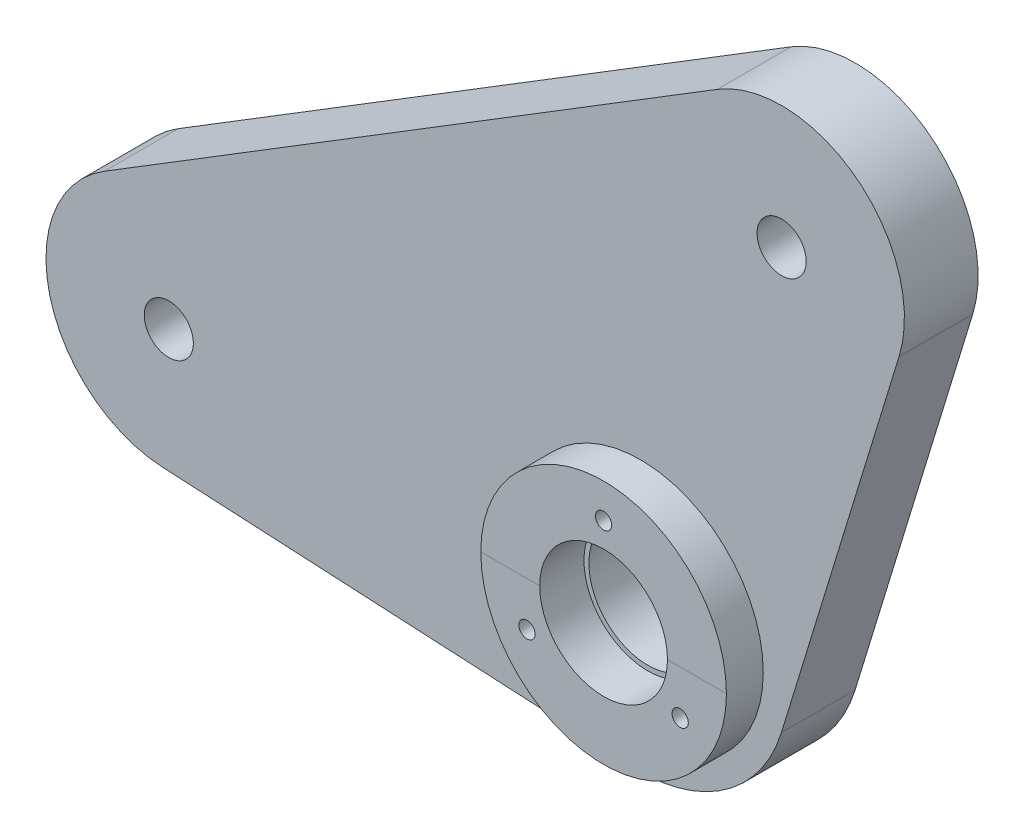
SolidWorks part; units mm, degrees
material "6061-T6 (SS)"
ref_plane "Front Plane" through (0, 0, 0) normal (0, 0, 1) x (1, 0, 0)
ref_plane "Top Plane" through (0, 0, 0) normal (0, 1, 0) x (1, 0, 0)
ref_plane "Right Plane" through (0, 0, 0) normal (1, 0, 0) x (0, 0, -1)
sketch "Layout_Reference" plane through (0, 0, 0) normal (0, 0, 1) x (1, 0, 0)
  line L0 (0, 0) -> (-96, 0) construction
  line L1 (0, 0) -> (28.736, 76.8) construction
  line L2 (-96, 0) -> (-232.8081, -375.877) construction
  line L3 (28.736, 76.8) -> (328.736, 76.8) construction
  dimension "D1" = 96
  dimension "D2" = 82
  dimension "D3" = 76.8
  dimension "D4" = 400
  dimension "D5" = 70
  dimension "D6" = 300
sketch "Rocker_Profile" plane through (0, 0, 0) normal (0, 0, 1) x (1, 0, 0)
  line L0 (-97.3021, -24.9661) -> (-1.5625, -29.9593)
  line L1 (28.6863, -8.7804) -> (52.6413, 69.483)
  line L2 (-109.1073, 21.2885) -> (15.6287, 98.0885)
  arc A0 (-1.5625, -29.9593) -> (28.6863, -8.7804) centre (0, 0) ccw
  arc A1 (52.6413, 69.483) -> (15.6287, 98.0885) centre (28.736, 76.8) ccw
  arc A2 (-109.1073, 21.2885) -> (-97.3021, -24.9661) centre (-96, 0) ccw
  dimension "D1" = 60
  dimension "D2" = 50
  dimension "D3" = 50
extrude "Baseline_Body" add sketch "Rocker_Profile" along normal mid plane 15
sketch "Sketch3" plane through (0, 0, 7.5) normal (0, 0, 1) x (1, 0, 0)
  circle A0 centre (-96, 0) radius 5
  circle A1 centre (28.736, 76.8) radius 5
  dimension "D1" = 10
  dimension "D2" = 10
extrude "Cut-Extrude1" cut sketch "Sketch3" against normal through all
sketch "Sketch4" plane through (0, 0, 0) normal (0, 0, 1) x (1, 0, 0)
  circle A0 centre (0, 0) radius 25
  dimension "D1" = 50
extrude "Boss-Extrude2" add sketch "Sketch4" along normal mid plane 30
sketch "Sketch5" plane through (0, 0, 15) normal (0, 0, 1) x (1, 0, 0)
  circle A0 centre (0, 0) radius 12
  dimension "D1" = 24
extrude "Cut-Extrude2" cut sketch "Sketch5" against normal through all
sketch "Sketch6" plane through (0, 0, 15) normal (0, 0, 1) x (1, 0, 0)
  circle A0 centre (0, 0) radius 13
  dimension "D1" = 26
extrude "Cut-Extrude3" cut sketch "Sketch6" against normal blind 9
sketch "Sketch7" plane through (0, 0, -15) normal (0, 0, -1) x (-1, 0, 0)
  circle A0 centre (0, 0) radius 13
  dimension "D1" = 26
extrude "Cut-Extrude4" cut sketch "Sketch7" against normal blind 9
hole_wizard "M4 Tapped Hole6" positions "Sketch13" profile "Sketch14" tap size "M4" standard "ISO"
sketch "Sketch13" plane through (0, 0, 15) normal (0, 0, 1) x (1, 0, 0)
  line L0 (0, 0) -> (0, 35.402) construction
  line L2 (0, 0) -> (31.5691, -18.2264) construction
  line L4 (0, 0) -> (-31.7239, -18.3158) construction
  circle A0 centre (0, 0) radius 18
  point P20 (0, 18)
  point P22 (15.5885, -9)
  point P24 (-15.5885, -9)
  dimension "D1" = 36
  dimension "D2" = 120
  dimension "D3" = 120
sketch "Sketch14" plane through (-15.5885, -9, 15) normal (1, 0, 0) x (0, -1, 0)
  line L0 (0, 0) -> (0, 9.9914)
  line L1 (0, 9.9914) -> (1.65, 9)
  line L2 (1.65, 9) -> (1.65, 0)
  line L5 (1.65, 0) -> (0, 0)
  line L10 (0, 9.9914) -> (-1.65, 9) construction
  line L11 (0, -6.35) -> (0, 107.95) construction
  dimension "Tap Drill Dia." = 3.3
  dimension "Tap Drill Depth" = 9
  dimension "Drill Angle" = 118
cosmetic thread "Hole Thread1" parameters "D1"=6, "D2"=4
cosmetic thread "Hole Thread2" parameters "D1"=6, "D2"=4
cosmetic thread "Hole Thread3" parameters "D1"=6, "D2"=4
hole_wizard "M4 Tapped Hole8" positions "Sketch15" profile "Sketch16" tap size "M4" standard "ISO"
sketch "Sketch15" plane through (0, 0, -15) normal (0, 0, -1) x (-1, 0, 0)
  line L0 (0, 0) -> (0, 31.1646) construction
  line L2 (0, 0) -> (31.1709, -17.9965) construction
  line L4 (0, 0) -> (-29.5586, -17.0657) construction
  circle A0 centre (0, 0) radius 18
  point P21 (0, 18)
  point P23 (15.5855, -8.9983)
  point P25 (-15.5885, -9)
  dimension "D1" = 36
  dimension "D2" = 120
  dimension "D3" = 120
sketch "Sketch16" plane through (15.5885, -9, -15) normal (1, 0, 0) x (0, 1, 0)
  line L0 (0, 0) -> (0, 9.9914)
  line L1 (0, 9.9914) -> (1.65, 9)
  line L2 (1.65, 9) -> (1.65, 0)
  line L5 (1.65, 0) -> (0, 0)
  line L10 (0, 9.9914) -> (-1.65, 9) construction
  line L11 (0, -6.35) -> (0, 107.95) construction
  dimension "Tap Drill Dia." = 3.3
  dimension "Tap Drill Depth" = 9
  dimension "Drill Angle" = 118
cosmetic thread "Hole Thread4" parameters "D1"=6, "D2"=4
cosmetic thread "Hole Thread5" parameters "D1"=6, "D2"=4
cosmetic thread "Hole Thread6" parameters "D1"=6, "D2"=4
split line "Split Line1"
ref_point "Point_Damper_Centre"
